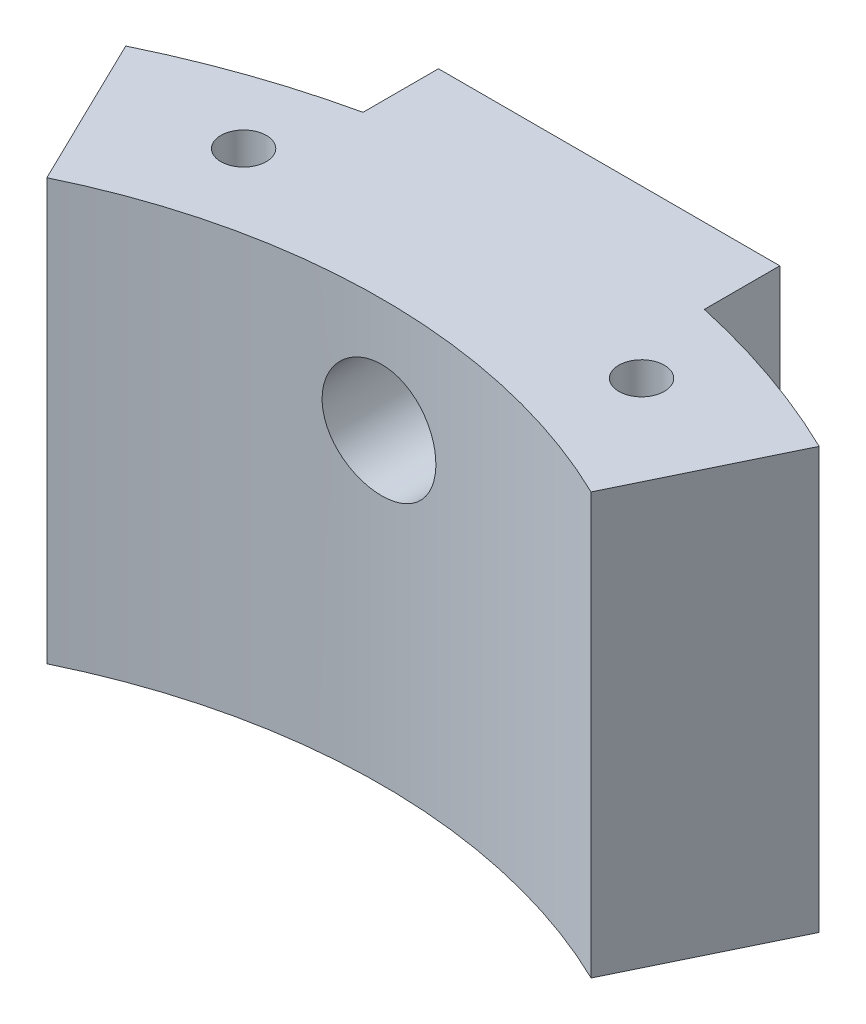
SolidWorks part; units mm, degrees
material "ABS"
ref_plane "Front Plane" through (0, 0, 0) normal (0, 0, 1) x (1, 0, 0)
ref_plane "Top Plane" through (0, 0, 0) normal (0, 1, 0) x (1, 0, 0)
ref_plane "Right Plane" through (0, 0, 0) normal (1, 0, 0) x (0, 0, -1)
sketch "Sketch1" plane through (0, 0, 0) normal (0, 1, 0) x (1, 0, 0)
  line L0 (0, 0) -> (6.5582, -13.4904)
  line L1 (60.9497, 0) -> (54.3915, -13.4904)
  arc A0 (0, 0) -> (60.9497, 0) centre (30.4748, -62.6878) cw
  arc A1 (6.5582, -13.4904) -> (54.3915, -13.4904) centre (30.4748, -62.6878) cw
  dimension "D1" = 15
extrude "Boss-Extrude1" add sketch "Sketch1" along normal blind 37
sketch "Sketch2" plane through (0, 37, 0) normal (0, 1, 0) x (1, 0, 0)
  circle A2 centre (12.9859, -2.6224) radius 2
  circle A3 centre (47.9637, -2.6224) radius 2
  dimension "D1" = 4
extrude "Cut-Extrude1" cut sketch "Sketch2" against normal through all
sketch "Sketch3" plane through (0, 37, 0) normal (0, 1, 0) x (1, 0, 0)
  line L2 (15.4748, 12.015) -> (45.4748, 12.015)
  line L3 (45.4748, 12.015) -> (45.4748, 4.1184)
  line L4 (45.4748, 4.1184) -> (15.4748, 4.1184)
  line L5 (15.4748, 12.015) -> (15.4748, 4.1184)
  point P15 (30.4748, 4.1184)
extrude "Boss-Extrude2" add sketch "Sketch3" against normal blind 48
sketch "Sketch4" plane through (0, 0, -4.1184) normal (0, 0, 1) x (1, 0, 0)
  line L0 (15.4748, -11) -> (15.4748, 0) construction
  line L1 (45.4748, 0) -> (15.4748, 0)
  line L2 (45.4748, 0) -> (45.4748, -6)
  line L3 (45.4748, -6) -> (15.4748, -6)
  line L4 (15.4748, 0) -> (15.4748, -6)
  dimension "D1" = 6
extrude "Cut-Extrude2" cut sketch "Sketch4" against normal blind 4
fillet "Fillet1" radius 10 2 edges at (15.4748, -11, -8.0667) (45.4748, -11, -8.0667)
sketch "Sketch5" plane through (0, 0, -12.015) normal (0, 0, -1) x (-1, 0, 0)
  line L0 (-45.4748, 37) -> (-15.4748, 37) construction
  circle A0 centre (-30.4748, 27) radius 5
  dimension "D1" = 10
  dimension "D2" = 10
extrude "Cut-Extrude3" cut sketch "Sketch5" against normal through all
sketch "Sketch7" plane through (0, 0, -12.015) normal (0, 0, -1) x (-1, 0, 0)
  line L0 (-21.5361, 1.4539) -> (-26.1998, 0)
  line L1 (-34.426, 3.6737) -> (-38.9602, 5.6642)
  arc A0 (-26.1998, 0) -> (-21.5361, 1.4539) centre (-24.0106, 1.1845) cw
  arc A1 (-34.426, 3.6737) -> (-38.9602, 5.6642) centre (-36.8827, 4.237) cw
extrude "Boss-Extrude3" add sketch "Sketch7" along normal blind 1
sketch "Sketch8" plane through (0, 0, -13.015) normal (0, 0, -1) x (-1, 0, 0)
  line L0 (-23.0227, 0.9904) -> (-25.0369, 0.3625)
  line L1 (-26.1998, 0) -> (-21.5361, 1.4539) construction
  line L2 (-26.1998, 0) -> (-21.5361, 1.4539) construction
  line L3 (-35.7508, 4.2552) -> (-37.8939, 5.1961)
  line L4 (-34.426, 3.6737) -> (-38.9602, 5.6642) construction
  line L5 (-34.426, 3.6737) -> (-38.9602, 5.6642) construction
  arc A0 (-23.0227, 0.9904) -> (-25.0369, 0.3625) centre (-24.1419, 1.0361) ccw
  arc A1 (-35.7508, 4.2552) -> (-37.8939, 5.1961) centre (-36.9613, 4.4092) cw
extrude "Cut-Extrude4" cut sketch "Sketch8" against normal blind 0.5
